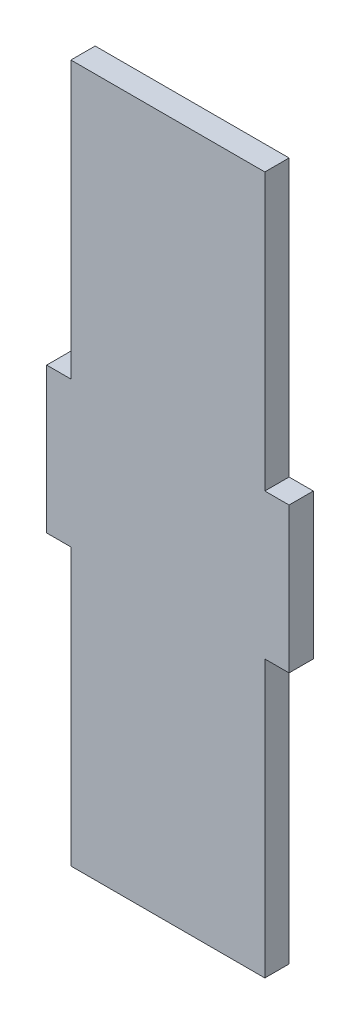
SolidWorks part; units mm, degrees
ref_plane "Front Plane" through (0, 0, 0) normal (0, 0, 1) x (1, 0, 0)
ref_plane "Top Plane" through (0, 0, 0) normal (0, 1, 0) x (1, 0, 0)
ref_plane "Right Plane" through (0, 0, 0) normal (1, 0, 0) x (0, 0, -1)
sketch "Sketch1" plane through (0, 0, 0) normal (0, 0, 1) x (1, 0, 0)
  line L1 (-20, -72) -> (20, -72)
  line L2 (-20, -72) -> (-20, -15)
  line L3 (-20, 72) -> (20, 72)
  line L4 (20, -72) -> (20, -15)
  line L5 (-20, -72) -> (20, 72) construction
  line L6 (-20, 72) -> (20, -72) construction
  line L8 (-20, 15) -> (-25, 15)
  line L9 (-25, 15) -> (-25, -15)
  line L10 (-25, -15) -> (-20, -15)
  line L11 (0, -55) -> (0, 55) construction
  line L12 (25, 15) -> (25, -15)
  line L13 (20, 15) -> (25, 15)
  line L16 (25, -15) -> (20, -15)
  line L17 (-20, 15) -> (-20, 72)
  line L18 (20, 15) -> (20, 72)
  point P0 (0, 0)
  dimension "D1" = 40
  dimension "D2" = 144
  dimension "D5" = 5
extrude "Boss-Extrude1" add sketch "Sketch1" along normal blind 5
